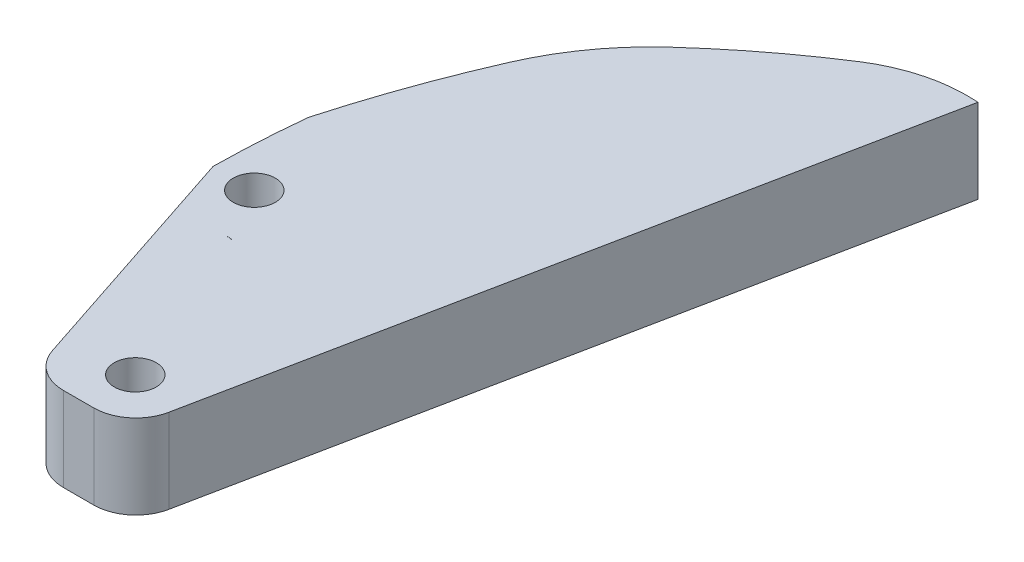
SolidWorks part; units mm, degrees
ref_plane "Front Plane" through (0, 0, 0) normal (0, 0, 1) x (1, 0, 0)
ref_plane "Top Plane" through (0, 0, 0) normal (0, 1, 0) x (1, 0, 0)
ref_plane "Right Plane" through (0, 0, 0) normal (1, 0, 0) x (0, 0, -1)
sketch "Sketch2" plane through (0, 0, 0) normal (0, 1, 0) x (1, 0, 0)
  line L0 (0.4117, 0.7667) -> (1.8554, 0.7667)
  line L3 (-5.2545, 13.5468) -> (-1.4874, 2.1395)
  line L4 (3.8157, 2.3703) -> (10.287, 34.3723)
  line L8 (0.4117, 0.7667) -> (1.8554, 0.7667)
  circle A0 centre (1.4787, 3.1157) radius 1
  arc A1 (-1.7609, 10.971) -> (-2.0202, 10.9998) centre (-2, 10) ccw
  arc A2 (1.8554, 0.7667) -> (3.8157, 2.3703) centre (1.8554, 2.7667) ccw
  circle A3 centre (-3.2942, 13.5468) radius 1
  arc A5 (-2.0202, 10.9998) -> (-1.7609, 10.971) centre (-1, 19) ccw
  arc A7 (-1.4874, 2.1395) -> (0.4117, 0.7667) centre (0.4117, 2.7667) ccw
  arc A10 (3.777, 2.2122) -> (3.783, 2.2085) centre (13.0997, 17.247) ccw
  arc A11 (6.4946, 33.6582) -> (-1.354, 27.3148) centre (26.5907, 0.7667) ccw
  arc A13 (8.2622, 34.2633) -> (6.4946, 33.6582) centre (13.0997, 17.247) ccw
  arc A14 (10.287, 34.3723) -> (8.2622, 34.2633) centre (9.7795, 24.9355) ccw
  arc A17 (10.287, 34.3723) -> (8.2622, 34.2633) centre (9.7795, 24.9355) ccw
  arc A18 (-1.354, 27.3148) -> (-5.0039, 17.839) centre (45.9805, 3.6415) ccw
  arc A20 (-5.0039, 17.839) -> (-5.2545, 13.5468) centre (40.4186, 13.0336) ccw
  dimension "D2" = 2
  dimension "D1" = 2
extrude "Boss-Extrude2" add sketch "Sketch2" along normal blind 4
fillet "Fillet1" radius 13 1 edges at (-1.354, 2, -27.3148)
fillet "Fillet2" radius 7 1 edges at (8.2622, 2, -34.2633)
fillet "Fillet4" radius 7 1 edges at (6.4946, 2, -33.6582)
